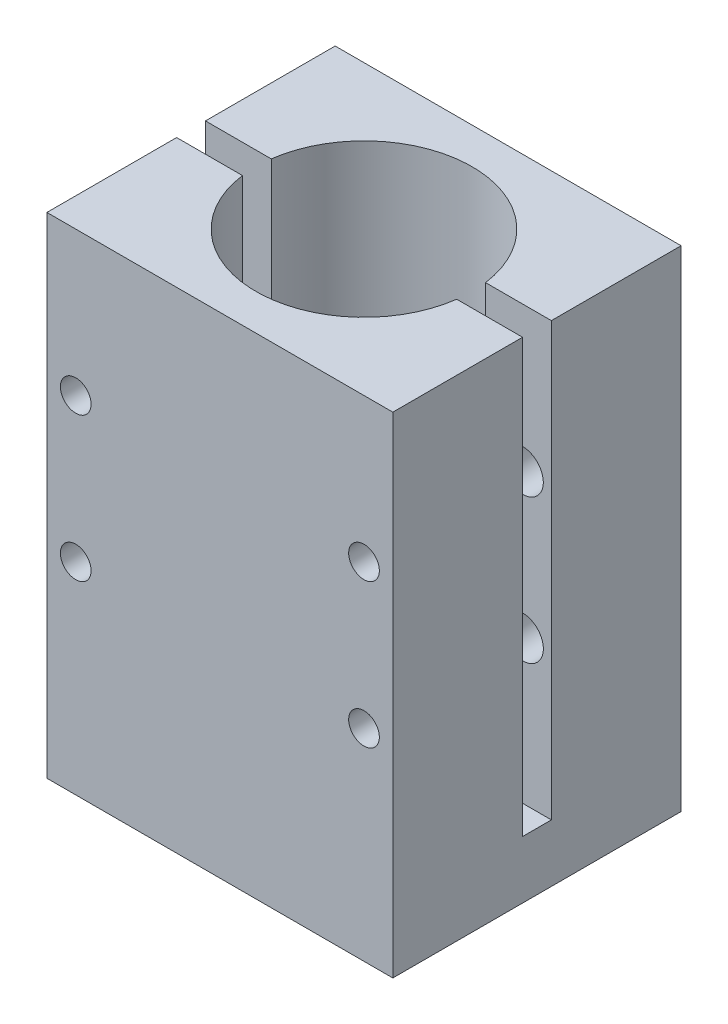
SolidWorks part; units mm, degrees
ref_plane "Front Plane" through (0, 0, 0) normal (0, 0, 1) x (1, 0, 0)
ref_plane "Top Plane" through (0, 0, 0) normal (0, 1, 0) x (1, 0, 0)
ref_plane "Right Plane" through (0, 0, 0) normal (1, 0, 0) x (0, 0, -1)
sketch "Sketch1" plane through (0, 0, 0) normal (0, 1, 0) x (1, 0, 0)
  line L1 (-29.21, 0) -> (26.67, 0)
  line L2 (-29.21, 0) -> (-29.21, -25.4)
  line L3 (-29.21, -25.4) -> (26.67, -25.4)
  line L4 (26.67, 0) -> (26.67, -25.4)
  dimension "D1" = 25.4
  dimension "D2" = 55.88
extrude "Extrude1" add sketch "Sketch1" along normal blind 101.6
ref_plane "Plane1" through (0, 0, 17.78) normal (0, 0, 1) x (1, 0, 0)
ref_plane "Plane2" through (0, 101.6, 0) normal (0, 1, 0) x (-1, 0, 0)
sketch "Sketch4" plane through (0, 101.6, 0) normal (0, 1, 0) x (-1, 0, 0)
  line L0 (-26.67, 25.4) -> (-26.67, 0) construction
  line L1 (-26.67, 0) -> (29.21, 0) construction
  circle A0 centre (1.27, 12.7) radius 9.525
  dimension "D1" = 19.05
  dimension "D2" = 12.7
  dimension "D3" = 27.94
extrude "Cut-Extrude2" cut sketch "Sketch4" against normal blind 58.42
ref_plane "Plane3" through (26.67, 0, 0) normal (1, 0, 0) x (0, 0, -1)
ref_plane "Plane4" through (-29.21, 0, 0) normal (-1, 0, 0) x (0, 0, 1)
sketch "Sketch7" plane through (26.67, 0, 0) normal (1, 0, 0) x (0, 0, -1)
  line L0 (-25.4, 101.6) -> (-25.4, 0) construction
  line L1 (-25.4, 101.6) -> (0, 101.6)
  line L2 (-25.4, 101.6) -> (-25.4, 0)
  line L3 (-25.4, 0) -> (0, 0)
  line L4 (0, 101.6) -> (0, 0)
  line L5 (0, 101.6) -> (0, 0) construction
  dimension "D1" = 101.6
extrude "Cut-Extrude5" cut sketch "Sketch7" against normal blind 12.7
sketch "Sketch8" plane through (-29.21, 0, 0) normal (-1, 0, 0) x (0, 0, 1)
  line L0 (13.97, 101.6) -> (-13.97, 101.6) construction
  line L1 (0, 101.6) -> (25.4, 101.6)
  line L2 (0, 101.6) -> (0, 0)
  line L3 (0, 0) -> (25.4, 0)
  line L4 (25.4, 101.6) -> (25.4, 0)
  line L5 (0, 101.6) -> (0, 0) construction
  line L6 (25.4, 101.6) -> (25.4, 0) construction
extrude "Cut-Extrude6" cut sketch "Sketch8" against normal blind 12.7
sketch "Sketch15" plane through (0, 101.6, 0) normal (0, 1, 0) x (-1, 0, 0)
  line L0 (-13.97, 25.4) -> (-13.97, 0) construction
  line L1 (-13.97, 13.97) -> (-8.17, 13.97)
  line L2 (-13.97, 13.97) -> (-13.97, 11.43)
  line L3 (-13.97, 11.43) -> (-8.17, 11.43)
  line L4 (-8.17, 13.97) -> (-8.17, 11.43)
  line L5 (16.51, 25.4) -> (-13.97, 25.4) construction
  line L6 (-13.97, 0) -> (16.51, 0) construction
  circle A0 centre (1.27, 12.7) radius 9.525 construction
  dimension "D1" = 11.43
  dimension "D2" = 11.43
extrude "Cut-Extrude10" cut sketch "Sketch15" against normal blind 58.42
sketch "Sketch20" plane through (0, 101.6, 0) normal (0, 1, 0) x (-1, 0, 0)
  circle A0 centre (1.27, 12.7) radius 2.54
hole_wizard "#8-32 Tapped Hole2" [suppressed] positions "3DSketch2" profile "Sketch22" tap size "#8-32" standard "Ansi Inch"
sketch3d "3DSketch2" [suppressed]
  point P0 (-1.27, 45.72, 17.78)
sketch "Sketch22" [suppressed] plane through (-1.27, 45.72, 17.78) normal (1, 0, 0) x (0, 1, 0)
  line L0 (0, 0) -> (0, 7.62)
  line L1 (0, 7.62) -> (1.7272, 7.62)
  line L2 (1.7272, 7.62) -> (1.7272, 0)
  line L5 (1.7272, 0) -> (0, 0)
  line L11 (0, -6.35) -> (0, 107.95) construction
  dimension "Thru Tap Drill Dia." = 3.4544
  dimension "Thru Tap Drill Depth" = 7.62
cosmetic thread "Hole Thread2" [suppressed] parameters "D2"=4.1656
ref_plane "Plane6" through (0, 0, 0) normal (0, 0, -1) x (-1, 0, 0)
sketch "Sketch25" plane through (0, 0, 0) normal (0, 0, -1) x (-1, 0, 0)
  line L0 (-13.97, 101.6) -> (16.51, 101.6) construction
  line L1 (-13.97, 0) -> (-13.97, 101.6) construction
  circle A0 centre (-11.43, 68.58) radius 3.2933
  dimension "D1" = 33.02
  dimension "D2" = 2.54
hole_wizard "#27 (0.144) Diameter Hole1" positions "3DSketch4" profile "Sketch27" hole size "#27" standard "Ansi Inch"
sketch3d "3DSketch4"
  point P0 (11.43, 68.58, 0)
sketch "Sketch27" plane through (11.43, 68.58, 0) normal (1, 0, 0) x (0, 1, 0)
  line L0 (0, 0) -> (0, 15.0689)
  line L1 (0, 15.0689) -> (1.8288, 13.97)
  line L2 (1.8288, 13.97) -> (1.8288, 0)
  line L5 (1.8288, 0) -> (0, 0)
  line L10 (0, 15.0689) -> (-1.8288, 13.97) construction
  line L11 (0, -6.35) -> (0, 107.95) construction
  dimension "Hole Dia." = 3.6576
  dimension "Hole Depth" = 13.97
  dimension "Drill Angle" = 118
sketch "Sketch29" plane through (0, 0, 0) normal (0, 0, -1) x (-1, 0, 0)
  circle A0 centre (-11.4343, 55.88) radius 2.7128
  dimension "D1" = 12.7
hole_wizard "#27 (0.144) Diameter Hole2" positions "3DSketch5" profile "Sketch30" hole size "#27" standard "Ansi Inch"
sketch3d "3DSketch5"
  point P0 (11.4343, 55.88, 0)
sketch "Sketch30" plane through (11.4343, 55.88, 0) normal (1, 0, 0) x (0, 1, 0)
  line L0 (0, 0) -> (0, 15.0689)
  line L1 (0, 15.0689) -> (1.8288, 13.97)
  line L2 (1.8288, 13.97) -> (1.8288, 0)
  line L5 (1.8288, 0) -> (0, 0)
  line L10 (0, 15.0689) -> (-1.8288, 13.97) construction
  line L11 (0, -6.35) -> (0, 107.95) construction
  dimension "Hole Dia." = 3.6576
  dimension "Hole Depth" = 13.97
  dimension "Drill Angle" = 118
ref_plane "Plane7" through (0, 0, 25.4) normal (0, 0, 1) x (1, 0, 0)
sketch "Sketch31" plane through (0, 0, 25.4) normal (0, 0, 1) x (1, 0, 0)
  line L0 (13.97, 101.6) -> (-13.97, 101.6) construction
  line L1 (13.97, 101.6) -> (13.97, 0) construction
  circle A0 centre (11.43, 68.58) radius 3.0138
  dimension "D1" = 33.02
  dimension "D2" = 2.54
hole_wizard "#6-32 Tapped Hole1" positions "3DSketch6" profile "Sketch33" tap size "#6-32" standard "Ansi Inch"
sketch3d "3DSketch6"
  point P0 (11.43, 68.58, 25.4)
sketch "Sketch33" plane through (11.43, 68.58, 25.4) normal (1, 0, 0) x (0, -1, 0)
  line L0 (0, 0) -> (0, 12.2427)
  line L1 (0, 12.2427) -> (1.3525, 11.43)
  line L2 (1.3525, 11.43) -> (1.3525, 0)
  line L5 (1.3525, 0) -> (0, 0)
  line L10 (0, 12.2427) -> (-1.3526, 11.43) construction
  line L11 (0, -6.35) -> (0, 107.95) construction
  dimension "Tap Drill Dia." = 2.7051
  dimension "Tap Drill Depth" = 11.43
  dimension "Drill Angle" = 118
cosmetic thread "Hole Thread4" parameters "D1"=7.112, "D2"=3.5052
sketch "Sketch34" plane through (0, 0, 25.4) normal (0, 0, 1) x (1, 0, 0)
  line L0 (13.97, 101.6) -> (13.97, 0) construction
  circle A0 centre (11.43, 55.88) radius 2.7896
  dimension "D1" = 12.7
  dimension "D2" = 2.54
hole_wizard "#6-32 Tapped Hole2" positions "3DSketch7" profile "Sketch35" tap size "#6-32" standard "Ansi Inch"
sketch3d "3DSketch7"
  point P0 (11.43, 55.88, 25.4)
sketch "Sketch35" plane through (11.43, 55.88, 25.4) normal (1, 0, 0) x (0, -1, 0)
  line L0 (0, 0) -> (0, 12.2427)
  line L1 (0, 12.2427) -> (1.3525, 11.43)
  line L2 (1.3525, 11.43) -> (1.3525, 0)
  line L5 (1.3525, 0) -> (0, 0)
  line L10 (0, 12.2427) -> (-1.3526, 11.43) construction
  line L11 (0, -6.35) -> (0, 107.95) construction
  dimension "Tap Drill Dia." = 2.7051
  dimension "Tap Drill Depth" = 11.43
  dimension "Drill Angle" = 118
cosmetic thread "Hole Thread5" parameters "D1"=7.112, "D2"=3.5052
sketch "Sketch36" plane through (0, 0, 0) normal (0, 0, -1) x (-1, 0, 0)
  line L1 (-13.97, 0) -> (-13.97, 101.6) construction
  circle A0 centre (1.27, 62.23) radius 2.6484
  dimension "D1" = 15.24
  dimension "D2" = 6.35
sketch "Sketch37" plane through (-29.21, 0, 0) normal (-1, 0, 0) x (0, 0, 1)
  line L0 (0, 16.764) -> (0, -16.764) construction
  line L1 (0, 38.1) -> (25.4, 38.1)
  line L2 (0, 38.1) -> (0, 0)
  line L3 (0, 0) -> (25.4, 0)
  line L4 (25.4, 38.1) -> (25.4, 0)
  dimension "D1" = 38.1
extrude "Cut-Extrude11" cut sketch "Sketch37" against normal through all
ref_plane "Plane8" through (0, 38.1, 0) normal (0, -1, 0) x (1, 0, 0)
sketch "Sketch40" plane through (0, 38.1, 0) normal (0, -1, 0) x (1, 0, 0)
  point P0 (-1.27, 19.05)
  dimension "D1" = 6.35
hole_wizard "#8-32 Tapped Hole3" positions "3DSketch8" profile "Sketch42" tap size "#8-32" standard "Ansi Inch" end condition through all
sketch3d "3DSketch8"
  point P0 (-1.27, 38.1, 19.05)
sketch "Sketch42" plane through (-1.27, 38.1, 19.05) normal (1, 0, 0) x (0, 0, -1)
  line L0 (0, 0) -> (0, 63.5)
  line L1 (0, 63.5) -> (1.7272, 63.5)
  line L2 (1.7272, 63.5) -> (1.7272, 0)
  line L5 (1.7272, 0) -> (0, 0)
  line L11 (0, -6.35) -> (0, 107.95) construction
  dimension "Thru Tap Drill Dia." = 3.4544
  dimension "Thru Tap Drill Depth" = 63.5
cosmetic thread "Hole Thread6" parameters "D2"=4.1656
ref_axis "Axis1" through (-1.27, 87.1976, 12.7) along (0, 1, 0)
pattern_circular "CirPattern2" count 2 over 360 about axis through (-1.27, 0, 12.7) along (0, 1, 0) of "#8-32 Tapped Hole3"
sketch "Sketch44" plane through (0, 0, 0) normal (0, 0, -1) x (-1, 0, 0)
  line L0 (16.51, 101.6) -> (16.51, 38.1) construction
  line L1 (-13.97, 101.6) -> (16.51, 101.6)
  line L2 (-13.97, 101.6) -> (-13.97, 81.28)
  line L3 (-13.97, 81.28) -> (16.51, 81.28)
  line L4 (16.51, 101.6) -> (16.51, 81.28)
  dimension "D1" = 20.32
extrude "Cut-Extrude12" cut sketch "Sketch44" against normal through all
pattern_circular "CirPattern3" count 2 over 360 about axis through (-1.27, 87.1976, 12.7) along (0, 1, 0) of "Cut-Extrude10"
hole_wizard "#6-32 Tapped Hole3" positions "3DSketch9" profile "Sketch46" tap size "#6-32" standard "Ansi Inch"
sketch3d "3DSketch9"
  line L0 (-16.51, 38.1, 25.4) -> (-16.51, 81.28, 25.4) construction
  line L1 (13.97, 81.28, 25.4) -> (-16.51, 81.28, 25.4) construction
  point P0 (-13.97, 68.58, 25.4)
  dimension "D1" = 2.54
  dimension "D2" = 12.7
cosmetic thread "Hole Thread7" parameters "D1"=7.112, "D2"=3.5052
sketch "Sketch46" plane through (-13.97, 68.58, 25.4) normal (1, 0, 0) x (0, -1, 0)
  line L0 (0, 0) -> (0, 14.7827)
  line L1 (0, 14.7827) -> (1.3525, 13.97)
  line L2 (1.3525, 13.97) -> (1.3525, 0)
  line L5 (1.3525, 0) -> (0, 0)
  line L10 (0, 14.7827) -> (-1.3526, 13.97) construction
  line L11 (0, -6.35) -> (0, 107.95) construction
  dimension "Tap Drill Dia." = 2.7051
  dimension "Tap Drill Depth" = 13.97
  dimension "Drill Angle" = 118
hole_wizard "#6-32 Tapped Hole4" positions "3DSketch10" profile "Sketch47" tap size "#6-32" standard "Ansi Inch"
sketch3d "3DSketch10"
  line L0 (-16.51, 38.1, 25.4) -> (-16.51, 81.28, 25.4) construction
  line L3 (13.97, 81.28, 25.4) -> (-16.51, 81.28, 25.4) construction
  point P0 (-13.97, 55.88, 25.4)
  dimension "D1" = 2.54
  dimension "D2" = 25.4
sketch "Sketch47" plane through (-13.97, 55.88, 25.4) normal (1, 0, 0) x (0, -1, 0)
  line L0 (0, 0) -> (0, 14.7827)
  line L1 (0, 14.7827) -> (1.3525, 13.97)
  line L2 (1.3525, 13.97) -> (1.3525, 0)
  line L5 (1.3525, 0) -> (0, 0)
  line L10 (0, 14.7827) -> (-1.3526, 13.97) construction
  line L11 (0, -6.35) -> (0, 107.95) construction
  dimension "Tap Drill Dia." = 2.7051
  dimension "Tap Drill Depth" = 13.97
  dimension "Drill Angle" = 118
cosmetic thread "Hole Thread8" parameters "D1"=7.112, "D2"=3.5052
hole_wizard "#27 (0.144) Diameter Hole3" positions "3DSketch11" profile "Sketch48" hole size "#27" standard "Ansi Inch"
sketch3d "3DSketch11"
  line L0 (-16.51, 81.28, 0) -> (-16.51, 38.1, 0) construction
  line L1 (13.97, 81.28, 0) -> (-16.51, 81.28, 0) construction
  point P0 (-13.97, 68.58, 0)
  dimension "D1" = 2.54
  dimension "D2" = 12.7
sketch "Sketch48" plane through (-13.97, 68.58, 0) normal (1, 0, 0) x (0, 1, 0)
  line L0 (0, 0) -> (0, 15.0689)
  line L1 (0, 15.0689) -> (1.8288, 13.97)
  line L2 (1.8288, 13.97) -> (1.8288, 0)
  line L5 (1.8288, 0) -> (0, 0)
  line L10 (0, 15.0689) -> (-1.8288, 13.97) construction
  line L11 (0, -6.35) -> (0, 107.95) construction
  dimension "Hole Dia." = 3.6576
  dimension "Hole Depth" = 13.97
  dimension "Drill Angle" = 118
hole_wizard "#27 (0.144) Diameter Hole4" positions "3DSketch12" profile "Sketch49" hole size "#27" standard "Ansi Inch"
sketch3d "3DSketch12"
  line L0 (13.97, 81.28, 0) -> (-16.51, 81.28, 0) construction
  line L1 (-16.51, 81.28, 0) -> (-16.51, 38.1, 0) construction
  point P0 (-13.97, 55.88, 0)
  dimension "D1" = 25.4
  dimension "D2" = 2.54
sketch "Sketch49" plane through (-13.97, 55.88, 0) normal (1, 0, 0) x (0, 1, 0)
  line L0 (0, 0) -> (0, 15.0689)
  line L1 (0, 15.0689) -> (1.8288, 13.97)
  line L2 (1.8288, 13.97) -> (1.8288, 0)
  line L5 (1.8288, 0) -> (0, 0)
  line L10 (0, 15.0689) -> (-1.8288, 13.97) construction
  line L11 (0, -6.35) -> (0, 107.95) construction
  dimension "Hole Dia." = 3.6576
  dimension "Hole Depth" = 13.97
  dimension "Drill Angle" = 118
